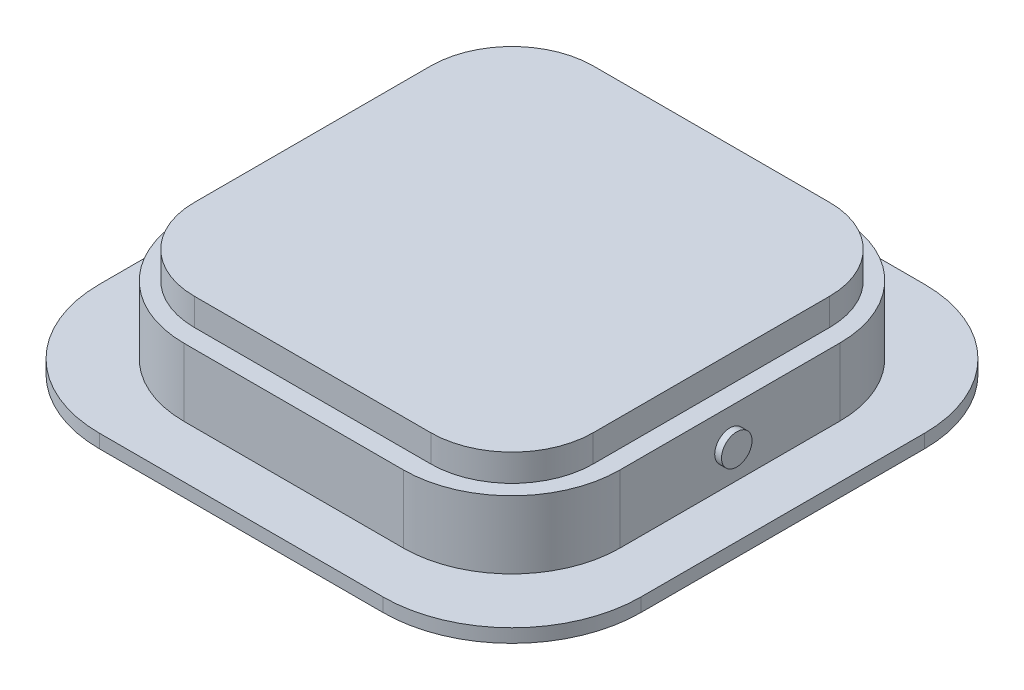
SolidWorks part; units mm, degrees
ref_plane "Front Plane" through (0, 0, 0) normal (0, 0, 1) x (1, 0, 0)
ref_plane "Top Plane" through (0, 0, 0) normal (0, 1, 0) x (1, 0, 0)
ref_plane "Right Plane" through (0, 0, 0) normal (1, 0, 0) x (0, 0, -1)
sketch "Sketch1" plane through (0, 0, 0) normal (0, 1, 0) x (1, 0, 0)
  line L1 (8.732, -14.732) -> (-8.732, -14.732)
  line L2 (14.732, -8.732) -> (14.732, 8.732)
  line L3 (8.732, 14.732) -> (-8.732, 14.732)
  line L4 (-14.732, -8.732) -> (-14.732, 8.732)
  line L5 (14.732, -14.732) -> (-14.732, 14.732) construction
  line L6 (14.732, 14.732) -> (-14.732, -14.732) construction
  arc A0 (-8.732, -14.732) -> (-14.732, -8.732) centre (-8.732, -8.732) cw
  arc A1 (8.732, -14.732) -> (14.732, -8.732) centre (8.732, -8.732) ccw
  arc A2 (14.732, 8.732) -> (8.732, 14.732) centre (8.732, 8.732) ccw
  arc A3 (-8.732, 14.732) -> (-14.732, 8.732) centre (-8.732, 8.732) ccw
  point P0 (0, 0)
  dimension "D3" = 6
  dimension "D4" = 6
  dimension "D5" = 6
  dimension "D6" = 6
  dimension "D1" = 29.464
  dimension "D2" = 29.464
extrude "Boss-Extrude1" add sketch "Sketch1" along normal blind 2
sketch "Sketch2" plane through (0, 0, 0) normal (0, -1, 0) x (1, 0, 0)
  line L1 (8.1, -16.1223) -> (-8.1, -16.1223)
  line L2 (16.1, -8.1223) -> (16.1, 8.1223)
  line L3 (8.1, 16.1223) -> (-8.1, 16.1223)
  line L4 (-16.1, -8.1223) -> (-16.1, 8.1223)
  line L5 (16.1, -16.1223) -> (-16.1, 16.1223) construction
  line L6 (16.1, 16.1223) -> (-16.1, -16.1223) construction
  arc A0 (8.1, -16.1223) -> (16.1, -8.1223) centre (8.1, -8.1223) ccw
  arc A1 (-8.1, -16.1223) -> (-16.1, -8.1223) centre (-8.1, -8.1223) cw
  arc A2 (16.1, 8.1223) -> (8.1, 16.1223) centre (8.1, 8.1223) ccw
  arc A3 (-8.1, 16.1223) -> (-16.1, 8.1223) centre (-8.1, 8.1223) ccw
  point P0 (0, 0)
  dimension "D3" = 8
  dimension "D1" = 32.2
  dimension "D2" = 32.2446
extrude "Boss-Extrude2" add sketch "Sketch2" along normal blind 5
sketch "Sketch3" plane through (0, -5, 0) normal (0, -1, 0) x (1, 0, 0)
  line L1 (10.475, -20) -> (-10.475, -20)
  line L2 (20, -10.475) -> (20, 10.475)
  line L3 (10.475, 20) -> (-10.475, 20)
  line L4 (-20, -10.475) -> (-20, 10.475)
  line L5 (20, -20) -> (-20, 20) construction
  line L6 (20, 20) -> (-20, -20) construction
  arc A0 (-10.475, -20) -> (-20, -10.475) centre (-10.475, -10.475) cw
  arc A1 (10.475, -20) -> (20, -10.475) centre (10.475, -10.475) ccw
  arc A2 (20, 10.475) -> (10.475, 20) centre (10.475, 10.475) ccw
  arc A3 (-10.475, 20) -> (-20, 10.475) centre (-10.475, 10.475) ccw
  point P0 (0, 0)
  dimension "D3" = 9.525
  dimension "D4" = 9.525
  dimension "D5" = 9.525
  dimension "D6" = 9.525
  dimension "D1" = 39.9999
  dimension "D2" = 40
extrude "Boss-Extrude3" add sketch "Sketch3" along normal blind 1
sketch "Sketch4" plane through (0, -6, 0) normal (0, -1, 0) x (1, 0, 0)
  line L1 (9.5, -13.25) -> (-9.5, -13.25)
  line L2 (12.5, -10.25) -> (12.5, 10.25)
  line L3 (9.5, 13.25) -> (-9.5, 13.25)
  line L4 (-12.5, -10.25) -> (-12.5, 10.25)
  line L5 (12.5, -13.25) -> (-12.5, 13.25) construction
  line L6 (12.5, 13.25) -> (-12.5, -13.25) construction
  arc A0 (-9.5, -13.25) -> (-12.5, -10.25) centre (-9.5, -10.25) cw
  arc A1 (9.5, -13.25) -> (12.5, -10.25) centre (9.5, -10.25) ccw
  arc A2 (12.5, 10.25) -> (9.5, 13.25) centre (9.5, 10.25) ccw
  arc A3 (-9.5, 13.25) -> (-12.5, 10.25) centre (-9.5, 10.25) ccw
  point P0 (0, 0)
  dimension "D3" = 3
  dimension "D4" = 3
  dimension "D5" = 3
  dimension "D6" = 3
  dimension "D1" = 25
  dimension "D2" = 26.5
extrude "Boss-Extrude4" add sketch "Sketch4" along normal blind 2.5
sketch "Sketch5" plane through (16.1, 0, 0) normal (1, 0, 0) x (0, 0, -1)
  line L0 (0, 0) -> (0, -5) construction
  line L1 (8.1223, -5) -> (-8.1223, -5) construction
  circle A0 centre (0, -2.5) radius 1.1276
extrude "Boss-Extrude5" add sketch "Sketch5" along normal blind 0.5
